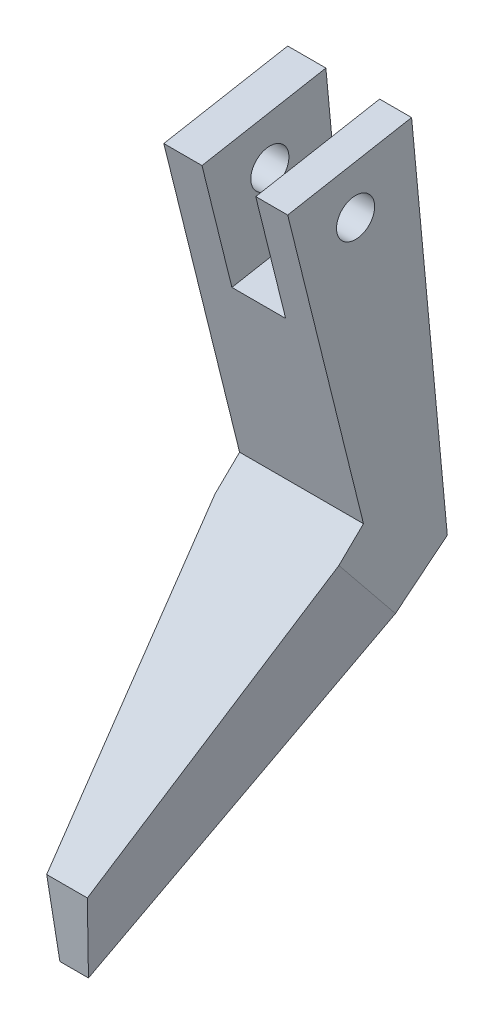
SolidWorks part; units mm, degrees
ref_plane "前视基准面" through (0, 0, 0) normal (0, 0, 1) x (1, 0, 0)
ref_plane "上视基准面" through (0, 0, 0) normal (0, 1, 0) x (1, 0, 0)
ref_plane "右视基准面" through (0, 0, 0) normal (1, 0, 0) x (0, 0, -1)
sketch "草图1" plane through (0, 0, 0) normal (1, 0, 0) x (0, 0, -1)
  line L0 (-117.4134, 203.9952) -> (12.5866, 227.5881)
  line L1 (12.5866, 227.5881) -> (50.0544, -170.6532)
  line L2 (50.0544, -170.6532) -> (-276.4838, -434.7987)
  line L3 (-276.4838, -434.7987) -> (-283.9773, -355.1504)
  line L4 (-283.9773, -355.1504) -> (-37.9026, -116.2829)
  line L5 (-37.9026, -116.2829) -> (-117.4134, 203.9952)
  dimension "D1" = 130
  dimension "D2" = 330
  dimension "D3" = 400
  dimension "D4" = 420
  dimension "D5" = 80
extrude "凸台-拉伸1" add sketch "草图1" along normal blind 130
sketch "草图2" plane through (0, -127.6284, -103.242) normal (0, -0.7775, -0.6289) x (1, 0, 0)
  line L0 (130, 138.4109) -> (80, 488.4109)
  line L1 (130, 488.4109) -> (130, 68.4109) construction
  line L2 (130, 488.4109) -> (0, 488.4109) construction
  line L3 (50, 488.4109) -> (0, 138.4109)
  line L4 (0, 488.4109) -> (0, 68.4109) construction
  line L5 (50, 488.4109) -> (0, 488.4109)
  line L6 (0, 488.4109) -> (0, 138.4109)
  line L7 (80, 488.4109) -> (130, 488.4109)
  line L8 (130, 488.4109) -> (130, 138.4109)
  dimension "D1" = 50
  dimension "D2" = 50
  dimension "D3" = 350
  dimension "D4" = 350
extrude "切除-拉伸1" cut sketch "草图2" against normal blind 130
sketch "草图3" plane through (0, 218.1197, 39.5853) normal (0, 0.9839, 0.1786) x (1, 0, 0)
  line L0 (40.061, 53.0241) -> (40.061, -79.0995)
  line L1 (130, 53.0241) -> (0, 53.0241) construction
  line L2 (130, -79.0995) -> (0, -79.0995) construction
  line L3 (40.061, -79.0995) -> (96.4615, -79.0995)
  line L4 (96.4615, -79.0995) -> (96.4615, 53.0241)
  line L5 (96.4615, 53.0241) -> (40.061, 53.0241)
extrude "切除-拉伸2" cut sketch "草图3" against normal blind 130
sketch "草图4" plane through (0, 0, 0) normal (-1, 0, 0) x (0, 0, 1)
  line L0 (-12.5866, 227.5881) -> (117.4134, 203.9952) construction
  line L1 (117.4134, 203.9952) -> (37.9026, -116.2829) construction
  circle A0 centre (46.204, 166.1787) radius 20
  point P5 (52.4134, 215.7916)
  dimension "D3" = 40
  dimension "D1" = 50
  dimension "D2" = 60
extrude "切除-拉伸4" cut sketch "草图4" against normal through all
